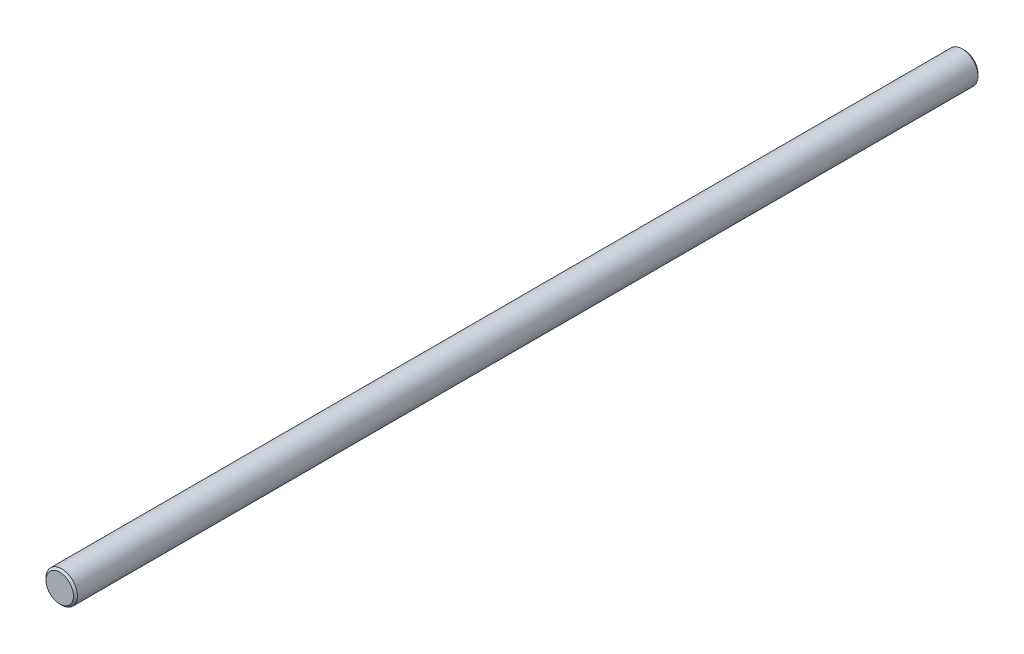
SolidWorks part; units mm, degrees
ref_plane "Plan de face" through (0, 0, 0) normal (0, 0, 1) x (1, 0, 0)
ref_plane "Plan de dessus" through (0, 0, 0) normal (0, 1, 0) x (1, 0, 0)
ref_plane "Plan de droite" through (0, 0, 0) normal (1, 0, 0) x (0, 0, -1)
sketch "Esquisse1" plane through (0, 0, 0) normal (0, 0, 1) x (1, 0, 0)
  circle A0 centre (0, 0) radius 4
  dimension "D1" = 8
extrude "Boss.-Extru.1" add sketch "Esquisse1" along normal mid plane 230
chamfer "Chanfrein1" distance 0.5 angle 45 2 edges at (4, 0, -115) (4, 0, 115)
